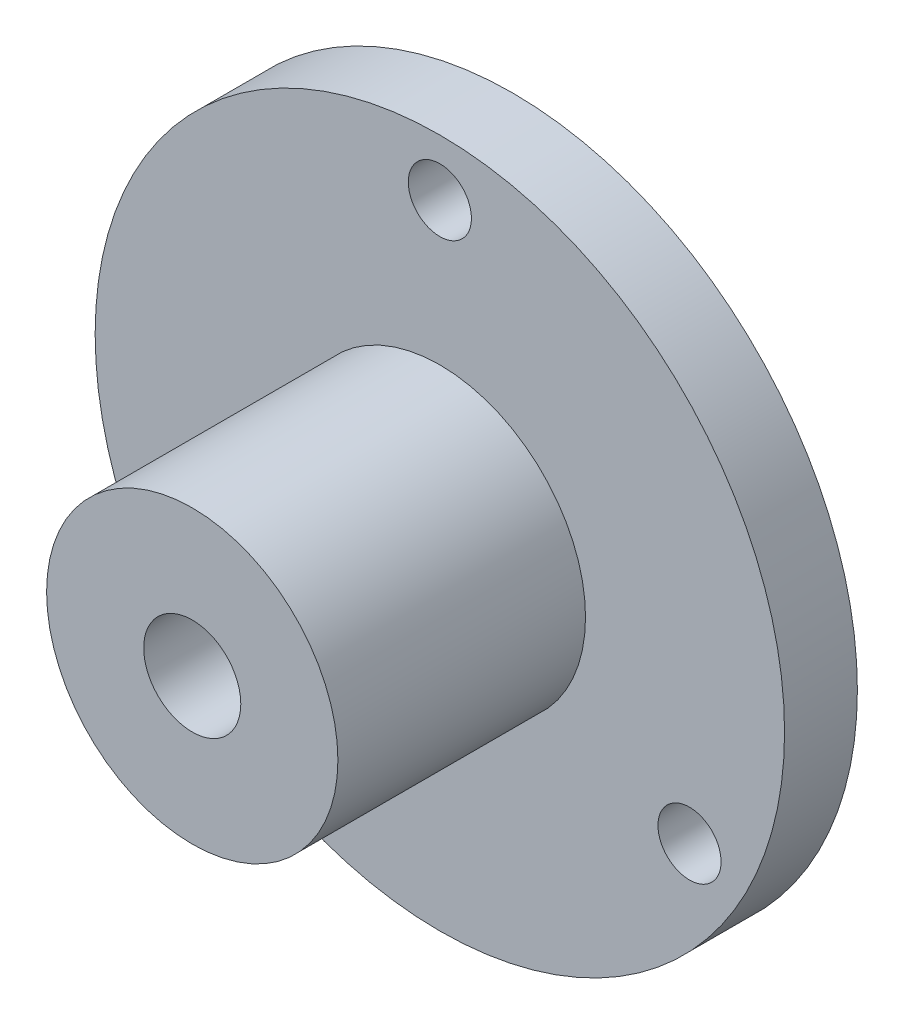
SolidWorks part; units mm, degrees
ref_plane "Front Plane" through (0, 0, 0) normal (0, 0, 1) x (1, 0, 0)
ref_plane "Top Plane" through (0, 0, 0) normal (0, 1, 0) x (1, 0, 0)
ref_plane "Right Plane" through (0, 0, 0) normal (1, 0, 0) x (0, 0, -1)
sketch "Sketch2" plane through (0, 0, 0) normal (0, 0, 1) x (1, 0, 0)
  circle A0 centre (0, 0) radius 28.4
  dimension "D1" = 56.8
extrude "Boss-Extrude1" add sketch "Sketch2" along normal blind 6
sketch "Sketch3" plane through (0, 0, 6) normal (0, 0, 1) x (1, 0, 0)
  circle A0 centre (0, 0) radius 12
  dimension "D1" = 24
extrude "Boss-Extrude2" add sketch "Sketch3" along normal blind 20.4
sketch "Sketch4" plane through (0, 0, 26.4) normal (0, 0, 1) x (1, 0, 0)
  circle A0 centre (0, 0) radius 4
  dimension "D1" = 8
extrude "Cut-Extrude1" cut sketch "Sketch4" against normal through all
sketch "Sketch5" plane through (0, 0, 0) normal (0, 0, -1) x (-1, 0, 0)
  line L0 (0, -23.75) -> (0, 23.75) construction
  circle A0 centre (0, 0) radius 23.75
  circle A1 centre (0, 23.75) radius 2.6
  dimension "D1" = 5.2
extrude "Cut-Extrude2" cut sketch "Sketch5" against normal through all contours A1
pattern_circular "CirPattern2" count 3 over 360 about axis through (0, 0, 0) along (0, 0, 1) of "Cut-Extrude2"
sketch "Sketch6" plane through (0, 0, 0) normal (1, 0, 0) x (0, 0, -1)
  line L0 (-26.4, 12) -> (-26.4, -12) construction
  circle A0 centre (-16.2, 0) radius 2.5
  dimension "D2" = 5
  dimension "D1" = 10.2
extrude "Cut-Extrude3" cut sketch "Sketch6" against normal through all contours A0
